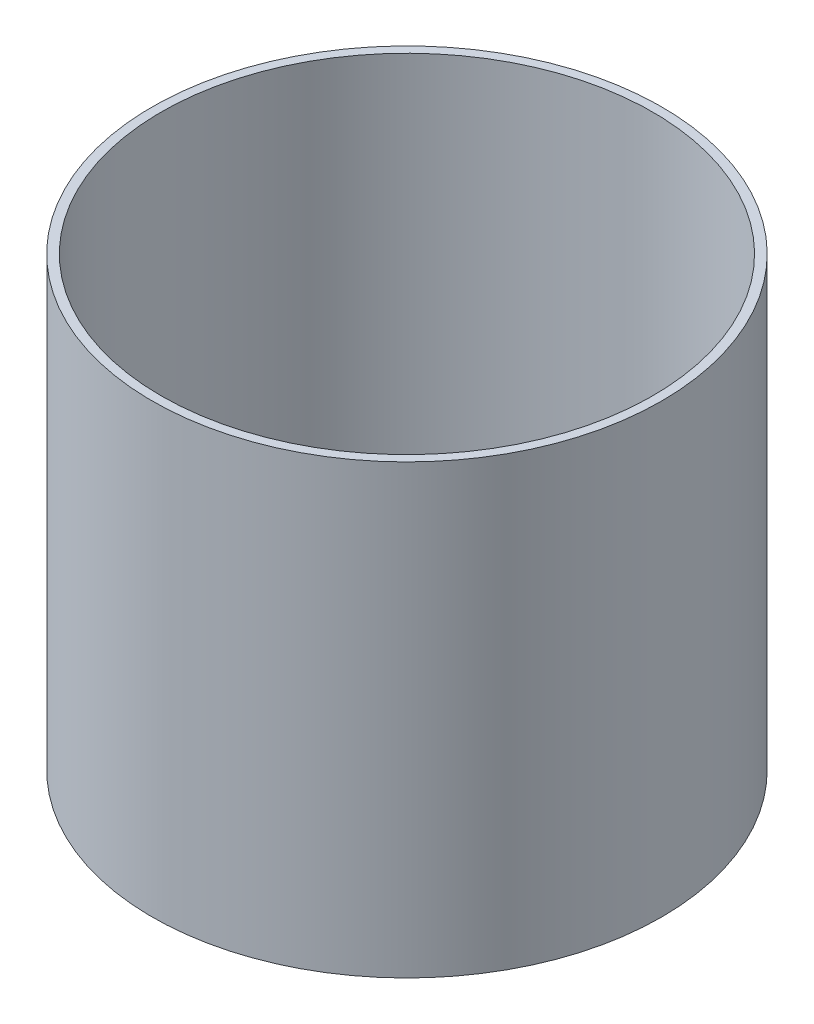
SolidWorks part; units mm, degrees
ref_plane "Alzado" through (0, 0, 0) normal (0, 0, 1) x (1, 0, 0)
ref_plane "Planta" through (0, 0, 0) normal (0, 1, 0) x (1, 0, 0)
ref_plane "Vista lateral" through (0, 0, 0) normal (1, 0, 0) x (0, 0, -1)
sketch "Croquis1" plane through (0, 0, 0) normal (0, 1, 0) x (1, 0, 0)
  circle A0 centre (0, 0) radius 5.5
extrude "Extruir-Lámina1" add sketch "Croquis1" along normal blind 10 thin
